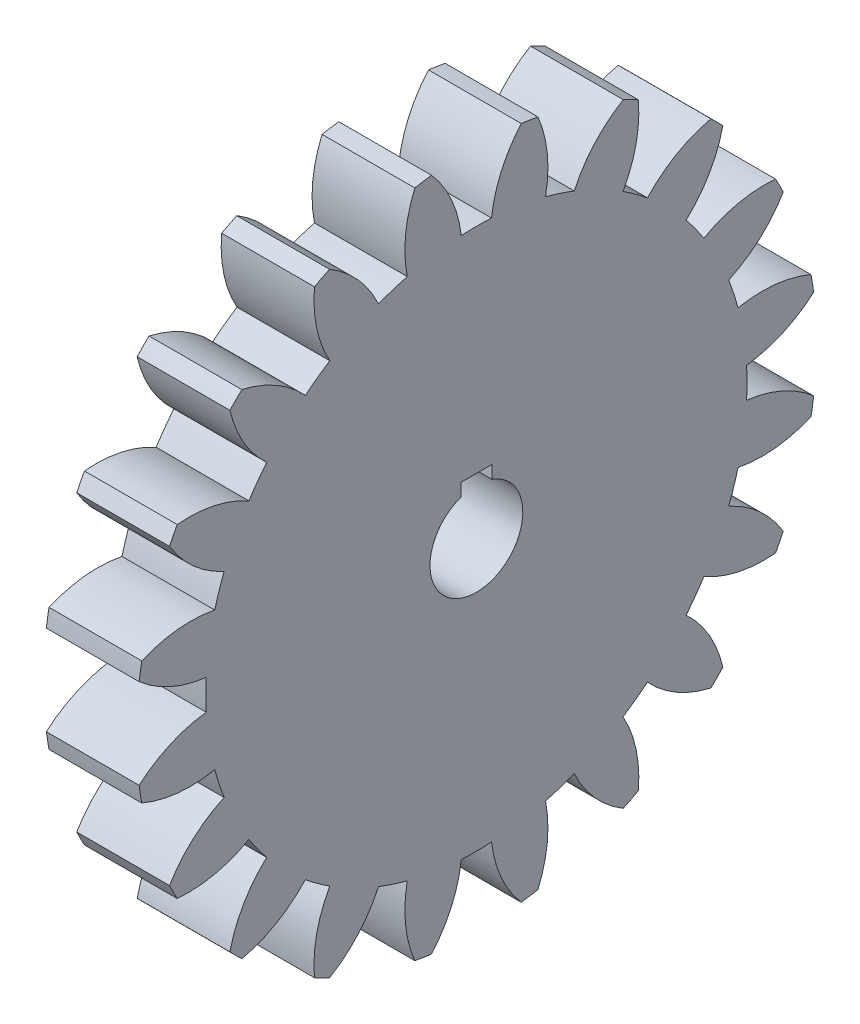
SolidWorks part; units mm, degrees
ref_plane "Plane1" through (0, 0, 0) normal (0, 0, 1) x (1, 0, 0)
ref_plane "Plane2" through (0, 0, 0) normal (0, 1, 0) x (1, 0, 0)
ref_plane "Plane3" through (0, 0, 0) normal (1, 0, 0) x (0, 0, -1)
other "Configuration Table"
sketch "HoldingSke" plane through (0, 0, 0) normal (0, 1, 0) x (1, 0, 0)
  line L0 (0, 0) -> (0.094, -0.0342)
  line L1 (-15, 0) -> (100, 0) construction
  line L2 (0, 0) -> (-2.1039, 2.3779)
  line L3 (0, 0) -> (-11.863, 4.5341)
  line L4 (0, 0) -> (8.1152, 2.9537)
  line L5 (0, 0) -> (-46.8476, -17.4728)
  line L6 (0, 0) -> (-24.8689, -16.7791)
  line L7 (-2.1039, 2.3779) -> (8.6586, 51.2059)
  line L8 (-76.2, 54.61) -> (-72.9, 54.61)
  line L9 (-71.009, 38.7566) -> (-53.1078, 45.2721)
  line L10 (-76.2, 71.12) -> (104.1128, 71.12)
  line L11 (0, 0) -> (-30, 0)
  line L12 (-76.2, 101.6) -> (-75.896, 101.6)
  line L13 (24.9733, 27.94) -> (52.9518, 28.4284)
  line L14 (24.9733, 27.94) -> (24.9743, 27.94)
  line L15 (24.9733, 27.94) -> (100.4006, 29.5858)
  line L16 (-63.627, -10) -> (-12.827, -10)
  circle A0 centre (0, 0) radius 15
  circle A1 centre (0, 0) radius 37.5
  circle A2 centre (0, 0) radius 37.5
  circle A3 centre (0, 0) radius 15
  dimension "MHD" = 75
  dimension "Hub_dia" = 75
  dimension "Bore" = 30
  dimension "MBD" = 30
  dimension "Num_teeth" = 20
  dimension "Pitch" = 0.1
  dimension "Overall_len" = 50
  dimension "Show_teeth" = 20
  dimension "Thickness" = 30
  dimension "OAL" = 50.0001
  dimension "T_dim" = 3.3
  dimension "Ap" = 20
  dimension "H" = 19.05
  dimension "Pitch_radius" = 180.3128
  dimension "Width" = 30
  dimension "Backlash" = 0.304
  dimension "Addendum_fac" = 1
  dimension "Dedendum_fac" = 1.25
  dimension "Clearance_fac" = 0.25
  dimension "Dedendum_add" = 0.001
  dimension "Module" = 10
sketch "BasProSke" plane through (0, 0, 0) normal (0, 1, 0) x (1, 0, 0)
  line L0 (-10, 0) -> (60, 0) construction
  line L1 (0, 0) -> (0, 110)
  line L2 (0, 0) -> (30, 0)
  line L3 (30, 0) -> (30, 110)
  line L4 (30, 110) -> (0, 110)
  dimension "Thickness" = 30
  dimension "Diameter" = 220
revolve "Base-Revolve" add sketch "BasProSke" angle 360 about L0
sketch "TooCutSke" plane through (0, 0, 0) normal (1, 0, 0) x (0, 0, -1)
  line L1 (0, 0) -> (0, 107) construction
  line L2 (0, 0) -> (-8.3777, 99.6485) construction
  line L3 (0, 0) -> (-31.2031, 197.0086) construction
  line L4 (-8.3777, 99.6485) -> (-15.6015, 98.5043) construction
  arc A0 (4.8838, 87.3626) -> (-4.8838, 87.3626) centre (0, 0) ccw
  arc A1 (14.5243, 109.0625) -> (-14.5243, 109.0625) centre (0, 0) ccw
  circle A2 centre (0, 0) radius 100 construction
  circle A3 centre (0, 0) radius 93.9693 construction
  arc A4 (-4.8838, 87.3626) -> (-14.5243, 109.0625) centre (-44.6116, 82.7044) ccw
  arc A5 (14.5243, 109.0625) -> (4.8838, 87.3626) centre (44.6116, 82.7044) ccw
  dimension "Root_dia" = 174.998
  dimension "Overcut_dia" = 220.0508
  dimension "Pitch_dia" = 200
  dimension "Base_dia" = 187.9385
  dimension "Flank_rad" = 40
  dimension "Half_ang" = 9
  dimension "Half_CT" = 7.3139
extrude "ToothCut" cut sketch "TooCutSke" along normal through all
fillet "Breaks" [suppressed] radius 0.2
fillet "RootFillets" [suppressed] radius 2.501
pattern_circular "TeethCuts" count 20 every 18 about axis through (-10, 0, 0) along (1, 0, 0) of "ToothCut", "RootFillets", "Breaks"
sketch "HubNeaOneSke" plane through (0, 0, 0) normal (-1, 0, 0) x (0, 0, 1)
  circle A0 centre (0, 0) radius 37.5
  dimension "Diameter" = 75
extrude "HubNearOne" add sketch "HubNeaOneSke" along normal blind 20.0001
sketch "HubNeaBotSke" plane through (0, 0, 0) normal (-1, 0, 0) x (0, 0, 1)
  circle A0 centre (0, 0) radius 37.5
  dimension "Diameter" = 75
extrude "HubNearBoth" [suppressed] add sketch "HubNeaBotSke" along normal blind 10
ref_plane "FarPln" through (30, 0, 0) normal (1, 0, 0) x (0, 0, -1)
sketch "HubFarSke" plane through (30, 0, 0) normal (1, 0, 0) x (0, 0, -1)
  circle A0 centre (0, 0) radius 37.5
  dimension "Diameter" = 75
extrude "HubFar" [suppressed] add sketch "HubFarSke" along normal blind 10
sketch "BorSke" plane through (0, 0, 0) normal (1, 0, 0) x (0, 0, -1)
  circle A0 centre (0, 0) radius 15
  dimension "Diameter" = 30
extrude "Bore" cut sketch "BorSke" along normal mid plane 100.0001
sketch "KeySke" plane through (0, 0, 0) normal (1, 0, 0) x (0, 0, -1)
  line L0 (-5, 0) -> (-5, 18.3)
  line L1 (-5, 18.3) -> (5, 18.3)
  line L2 (5, 18.3) -> (5, 0)
  line L3 (0, 0) -> (0, 34) construction
  line L4 (-5, 0) -> (5, 0)
  dimension "Offset" = 18.3
  dimension "Width" = 10
extrude "Keyway" cut sketch "KeySke" along normal mid plane 100.0001
pattern_circular "Keyway2" [suppressed] count 2 every 90 about axis through (-10, 0, 0) along (1, 0, 0)
equation "' \"Module@HoldingSke\" = 6.35"
equation "' \"Num_teeth@HoldingSke\" = 12"
equation "' \"Ap@HoldingSke\" =  20"
equation "' \"Ap@HoldingSke\" = 20"
equation "' \"Width@HoldingSke\" = 0.5 * 25.4"
equation "' \"Hub_dia@HoldingSke\"= 1 * 25.4"
equation "' \"Hub_dia@HoldingSke\" = 1 * 25.4"
equation "' \"Overall_len@HoldingSke\" = 1.0 * 25.4"
equation "' \"Bore@HoldingSke\" = 0.75 * 25.4"
equation "' \"T_dim@HoldingSke\" = 0.1 * 25.4"
equation "' \"Width@KeySke\" = 0.25 * 25.4"
equation "' \"Show_teeth@HoldingSke\" = 13"
equation "' \"Backlash@HoldingSke\" = 0.009 * 25.4"
equation "' \"Addendum_fac@HoldingSke\" = 1.0"
equation "' \"Dedendum_fac@HoldingSke\" = 1.25"
equation "' \"Dedendum_add@HoldingSke\" = 0.00005 * 25.4"
equation "' \"Clearance_fac@HoldingSke\" = 0.25"
equation "\"Pitch@HoldingSke\" = 1 / \"Module@HoldingSke\""
equation "\"Overcut_dia@TooCutSke\" = (\"Num_teeth@HoldingSke\" + 2 * \"Addendum_fac@HoldingSke\") / \"Pitch@HoldingSke\" + 0.002 * 25.4"
equation "\"Pitch_dia@TooCutSke\" = \"Num_teeth@HoldingSke\" / \"Pitch@HoldingSke\""
equation "\"Base_dia@TooCutSke\" = \"Num_teeth@HoldingSke\" / \"Pitch@HoldingSke\" * cos((\"Ap@HoldingSke\"  * 3.14159265 / 180))"
equation "\"Root_dia@TooCutSke\" = (\"Num_teeth@HoldingSke\" + 2) / \"Pitch@HoldingSke\" - 2 * (\"Addendum_fac@HoldingSke\" + \"Dedendum_fac@HoldingSke\") / \"Pitch@HoldingSke\" - \"Dedendum_add@HoldingSke\" * 2"
equation "\"Half_ang@TooCutSke\" = 180 / \"Num_teeth@HoldingSke\""
equation "\"Half_CT@TooCutSke\" = \"Num_teeth@HoldingSke\" / \"Pitch@HoldingSke\" * sin((3.14159265 / 2 / \"Num_teeth@HoldingSke\")) / 2 - 7 * \"Backlash@HoldingSke\" / 4"
equation "\"Flank_rad@TooCutSke\" = \"Num_teeth@HoldingSke\" / \"Pitch@HoldingSke\" / 5"
equation "\"Radius@RootFillets\" = \"Clearance_fac@HoldingSke\" / \"Pitch@HoldingSke\" + \"Dedendum_add@HoldingSke\""
equation "\"Break_rad@Breaks\" = 0.02 / \"Pitch@HoldingSke\""
equation "\"Thickness@HoldingSke\" = \"Width@HoldingSke\""
equation "\"OAL@HoldingSke\" = \"Thickness@HoldingSke\""
equation "\"MHD@HoldingSke\" = (\"Num_teeth@HoldingSke\" + 2) / \"Pitch@HoldingSke\" - 2 * (\"Addendum_fac@HoldingSke\" + \"Dedendum_fac@HoldingSke\")  / \"Pitch@HoldingSke\" - \"Dedendum_add@HoldingSke\" * 2"
equation "\"MBD@HoldingSke\" = (\"Num_teeth@HoldingSke\" + 2) / \"Pitch@HoldingSke\" - 2 * (\"Addendum_fac@HoldingSke\" + \"Dedendum_fac@HoldingSke\")  / \"Pitch@HoldingSke\" - \"Dedendum_add@HoldingSke\" * 2 - 0.002 * 25.4"
equation "\"MHD@HoldingSke\" = ((sgn( \"MHD@HoldingSke\" - \"Hub_dia@HoldingSke\" )-1)*( \"MHD@HoldingSke\" - \"Hub_dia@HoldingSke\" ))/-2+ \"Hub_dia@HoldingSke\""
equation "\"MBD@HoldingSke\" = ((sgn( \"MBD@HoldingSke\" - \"Bore@HoldingSke\" )-1)*( \"MBD@HoldingSke\" - \"Bore@HoldingSke\" ))/-2+ \"Bore@HoldingSke\""
equation "\"OAL@HoldingSke\" = ((sgn( \"OAL@HoldingSke\" - \"Overall_len@HoldingSke\" )+1)*( \"OAL@HoldingSke\" - \"Overall_len@HoldingSke\" ))/2 + \"Overall_len@HoldingSke\" + 0.000002 * 25.4"
equation "\"Num_teeth@TeethCuts\" = int( \"Show_teeth@HoldingSke\" ) + 1"
equation "\"Num_teeth@TeethCuts\" = ((sgn( \"Num_teeth@TeethCuts\" - \"Num_teeth@HoldingSke\" )-1)*( \"Num_teeth@TeethCuts\" - \"Num_teeth@HoldingSke\" ))/-2+ \"Num_teeth@HoldingSke\""
equation "\"Num_teeth@TeethCuts\" = ((sgn( \"Num_teeth@TeethCuts\" - 2.0)+1)*( \"Num_teeth@TeethCuts\" - 2.0))/2 +2.0"
equation "\"Angle@TeethCuts\" = 360.0 / \"Num_teeth@HoldingSke\""
equation "\"Diameter@BasProSke\" = (\"Num_teeth@HoldingSke\" + 2 * \"Addendum_fac@HoldingSke\") / \"Pitch@HoldingSke\""
equation "\"Thickness@BasProSke\"  = \"Thickness@HoldingSke\""
equation "' \"Fillet_rad@BasProSke\" =  \"Thickness@HoldingSke\" * 0.05"
equation "' \"Fillet_rad@BasProSke\" = \"Thickness@HoldingSke\" * 0.05"
equation "\"MHD@HoldingSke\" = ((sgn( \"MHD@HoldingSke\" - \"Root_dia@TooCutSke\" )-1)*( \"MHD@HoldingSke\" - \"Root_dia@TooCutSke\" ))/-2+ \"Root_dia@TooCutSke\""
equation "\"Diameter@HubNeaOneSke\" = \"MHD@HoldingSke\""
equation "\"Length@HubNearOne\" = \"OAL@HoldingSke\" - \"Thickness@BasProSke\""
equation "\"Diameter@HubNeaBotSke\" = \"MHD@HoldingSke\""
equation "\"Length@HubNearBoth\" = ( \"OAL@HoldingSke\" - \"Thickness@BasProSke\" ) / 2.0"
equation "\"Thickness@FarPln\" = \"Thickness@BasProSke\""
equation "\"Diameter@HubFarSke\" = \"MHD@HoldingSke\""
equation "\"Length@HubFar\" = ( \"OAL@HoldingSke\" - \"Thickness@BasProSke\" ) / 2.0"
equation "\"Diameter@BorSke\" = \"MBD@HoldingSke\""
equation "\"D1@Bore\" = \"OAL@HoldingSke\" * 2.0"
equation "\"D1@Keyway\" = \"OAL@HoldingSke\" * 2.0"
equation "\"Offset@KeySke\" = \"T_dim@HoldingSke\" + \"MBD@HoldingSke\" / 2.0"
